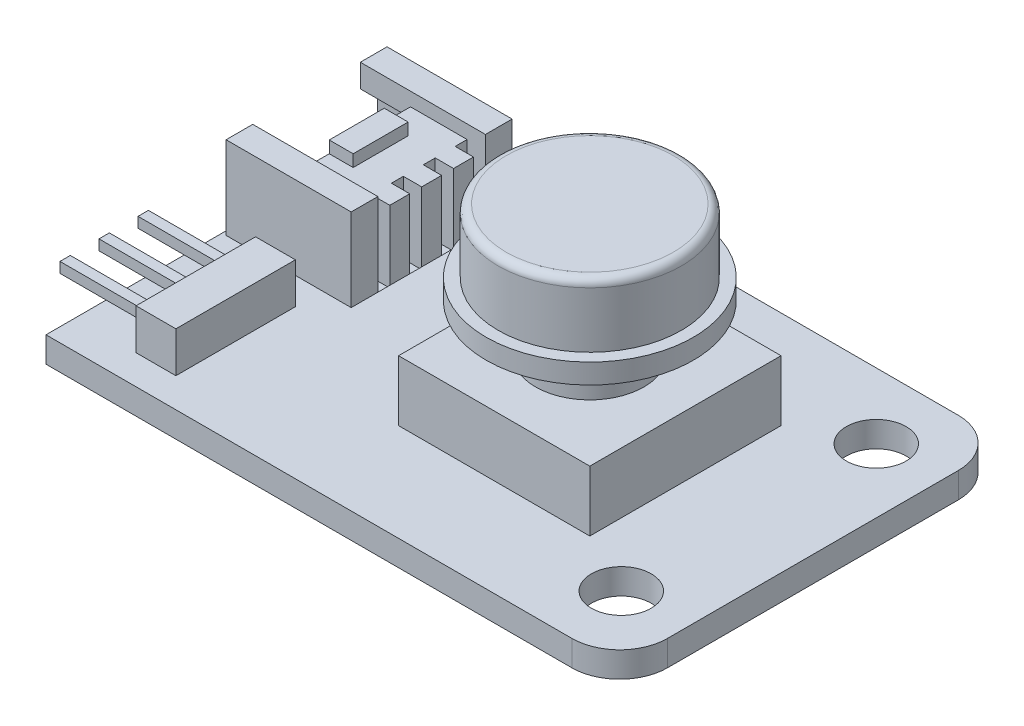
SolidWorks part; units mm, degrees
ref_plane "Front Plane" through (0, 0, 0) normal (0, 0, 1) x (1, 0, 0)
ref_plane "Top Plane" through (0, 0, 0) normal (0, 1, 0) x (1, 0, 0)
ref_plane "Right Plane" through (0, 0, 0) normal (1, 0, 0) x (0, 0, -1)
sketch "Sketch1" plane through (0, 0, 0) normal (0, 1, 0) x (1, 0, 0)
  line L0 (0, 0) -> (36, 0) construction
  line L1 (0, 12.125) -> (0, -12.125)
  line L2 (0, -12.125) -> (36, -12.125)
  line L3 (36, -12.125) -> (36, 12.125)
  line L4 (36, 12.125) -> (0, 12.125)
  dimension "D1" = 24.25
  dimension "D2" = 36
extrude "Boss-Extrude1" add sketch "Sketch1" along normal blind 1.6
sketch "Sketch2" plane through (0, 1.6, 0) normal (0, 1, 0) x (1, 0, 0)
  line L0 (0, 0) -> (36, 0) construction
  line L1 (36, -12.125) -> (36, 12.125) construction
  line L2 (31.975, -8) -> (31.975, 8) construction
  circle A0 centre (31.975, 8) radius 1.875
  circle A1 centre (31.975, -8) radius 1.875
  dimension "D1" = 12.25
  dimension "D2" = 3.75
  dimension "D3" = 2.15
extrude "Cut-Extrude1" cut sketch "Sketch2" against normal through all
fillet "Fillet1" radius 3 2 edges at (36, 0.8, -12.125) (36, 0.8, 12.125)
sketch "Sketch3" plane through (0, 1.6, 0) normal (0, 1, 0) x (1, 0, 0)
  line L0 (0, 0) -> (36, 0) construction
  line L1 (16, 6) -> (28, 6)
  line L2 (16, 6) -> (16, -6)
  line L3 (16, -6) -> (28, -6)
  line L4 (28, 6) -> (28, -6)
  line L5 (16, 6) -> (28, -6) construction
  line L6 (16, -6) -> (28, 6) construction
  line L7 (36, -9.125) -> (36, 9.125) construction
  point P0 (22, 0)
  dimension "D1" = 12
  dimension "D2" = 8
extrude "Boss-Extrude2" add sketch "Sketch3" along normal blind 3.8
sketch "Sketch4" plane through (0, 5.4, 0) normal (0, 1, 0) x (1, 0, 0)
  line L0 (16, 0) -> (28, 0) construction
  line L1 (16, 6) -> (16, -6) construction
  line L2 (28, -6) -> (28, 6) construction
  line L3 (22, 6) -> (22, -6) construction
  line L4 (28, 6) -> (16, 6) construction
  line L5 (16, -6) -> (28, -6) construction
  circle A0 centre (22, 0) radius 3.4
  dimension "D1" = 6.8
extrude "Boss-Extrude3" add sketch "Sketch4" along normal blind 3
sketch "Sketch5" plane through (0, 8.4, 0) normal (0, 1, 0) x (1, 0, 0)
  circle A0 centre (22, 0) radius 6.5
  dimension "D1" = 13
extrude "Boss-Extrude4" add sketch "Sketch5" along normal blind 1.25
sketch "Sketch6" plane through (0, 9.65, 0) normal (0, 1, 0) x (1, 0, 0)
  circle A0 centre (22, 0) radius 5.75
  dimension "D1" = 11.5
extrude "Boss-Extrude5" add sketch "Sketch6" along normal blind 4
fillet "Fillet2" radius 0.5 1 edges at (22, 13.65, 5.75)
sketch "Sketch7" plane through (0, 1.6, 0) normal (0, 1, 0) x (1, 0, 0)
  line L0 (0, 12.125) -> (0, -12.125) construction
  line L1 (3.8, -2.775) -> (6.3, -2.775)
  line L2 (3.8, -2.775) -> (3.8, -10.275)
  line L3 (3.8, -10.275) -> (6.3, -10.275)
  line L4 (6.3, -2.775) -> (6.3, -10.275)
  line L5 (0, -12.125) -> (33, -12.125) construction
  dimension "D1" = 2.5
  dimension "D2" = 7.5
  dimension "D3" = 3.8
  dimension "D4" = 1.85
extrude "Boss-Extrude6" add sketch "Sketch7" along normal blind 2.55
sketch "Sketch8" plane through (3.8, 0, 0) normal (-1, 0, 0) x (0, 0, 1)
  line L0 (2.775, 2.875) -> (10.275, 2.875) construction
  line L1 (2.775, 4.15) -> (2.775, 1.6) construction
  line L2 (10.275, 4.15) -> (10.275, 1.6) construction
  line L4 (3.75, 3.2) -> (4.4, 3.2)
  line L5 (3.75, 3.2) -> (3.75, 2.55)
  line L6 (3.75, 2.55) -> (4.4, 2.55)
  line L7 (4.4, 3.2) -> (4.4, 2.55)
  line L8 (3.75, 3.2) -> (4.4, 2.55) construction
  line L9 (3.75, 2.55) -> (4.4, 3.2) construction
  line L10 (6.2, 3.2) -> (6.85, 3.2)
  line L11 (6.2, 3.2) -> (6.2, 2.55)
  line L12 (6.2, 2.55) -> (6.85, 2.55)
  line L13 (6.85, 3.2) -> (6.85, 2.55)
  line L14 (6.2, 3.2) -> (6.85, 2.55) construction
  line L15 (6.2, 2.55) -> (6.85, 3.2) construction
  line L16 (8.65, 3.2) -> (9.3, 3.2)
  line L17 (8.65, 3.2) -> (8.65, 2.55)
  line L18 (8.65, 2.55) -> (9.3, 2.55)
  line L19 (9.3, 3.2) -> (9.3, 2.55)
  line L20 (8.65, 3.2) -> (9.3, 2.55) construction
  line L21 (8.65, 2.55) -> (9.3, 3.2) construction
  point P6 (4.075, 2.875)
  point P11 (6.525, 2.875)
  point P16 (8.975, 2.875)
  dimension "D1" = 0.65
  dimension "D2" = 1.8
  dimension "D3" = 1.8
extrude "Boss-Extrude7" add sketch "Sketch8" along normal blind 5.75
ref_plane "Plane1" through (0.25, 0, 0) normal (-1, 0, 0) x (0, 0, 1)
sketch "Sketch9" plane through (0.25, 0, 0) normal (-1, 0, 0) x (0, 0, 1)
  line L0 (-12.125, 1.6) -> (12.125, 1.6) construction
  line L1 (-9.025, 1.6) -> (1.075, 1.6)
  line L2 (-9.025, 1.6) -> (-9.025, 6.8)
  line L3 (-9.025, 6.8) -> (-7.35, 6.8)
  line L4 (1.075, 1.6) -> (1.075, 6.8)
  line L5 (-3.975, 1.6) -> (-3.975, 5.95) construction
  line L6 (-12.125, 1.6) -> (-12.125, 0) construction
  line L7 (-7.35, 6.8) -> (-7.35, 5.95)
  line L8 (-7.35, 5.95) -> (-0.6, 5.95)
  line L9 (-0.6, 6.8) -> (-0.6, 5.95)
  line L10 (-0.6, 6.8) -> (1.075, 6.8)
  point P13 (-8.1875, 6.8)
  dimension "D1" = 10.1
  dimension "D2" = 6.75
  dimension "D3" = 0.85
  dimension "D4" = 5.2
  dimension "D5" = 3.1
extrude "Boss-Extrude8" add sketch "Sketch9" against normal blind 7.85
sketch "Sketch10" plane through (0.25, 0, 0) normal (-1, 0, 0) x (0, 0, 1)
  line L24 (-8.425, 6.2) -> (-8.425, 2.2)
  line L25 (-8.425, 2.2) -> (0.475, 2.2)
  line L26 (0.475, 2.2) -> (0.475, 6.2)
  line L27 (0.475, 6.2) -> (0, 6.2)
  line L28 (0, 6.2) -> (0, 5.35)
  line L29 (0, 5.35) -> (-7.95, 5.35)
  line L30 (-7.95, 5.35) -> (-7.95, 6.2)
  line L31 (-7.95, 6.2) -> (-8.425, 6.2)
  line L32 (-8.425, 6.2) -> (-8.425, 2.2)
  line L33 (-8.425, 2.2) -> (0.475, 2.2)
  line L34 (0.475, 2.2) -> (0.475, 6.2)
  line L35 (0.475, 6.2) -> (0, 6.2)
  line L36 (0, 6.2) -> (0, 5.35)
  line L37 (0, 5.35) -> (-7.95, 5.35)
  line L38 (-7.95, 5.35) -> (-7.95, 6.2)
  line L39 (-7.95, 6.2) -> (-8.425, 6.2)
  dimension "D1" = 0.6
extrude "Cut-Extrude2" cut sketch "Sketch10" against normal blind 6.2
sketch "Sketch11" plane through (0, 5.95, 0) normal (0, 1, 0) x (1, 0, 0)
  line L0 (8.1, 0.6) -> (0.25, 0.6) construction
  line L1 (0.25, 7.35) -> (3.4, 7.35)
  line L2 (0.25, 7.35) -> (0.25, 0.6)
  line L3 (0.25, 0.6) -> (3.4, 0.6)
  line L4 (3.4, 7.35) -> (3.4, 0.6)
  dimension "D1" = 3.15
extrude "Cut-Extrude3" cut sketch "Sketch11" against normal blind 1
sketch "Sketch12" plane through (0, 2.2, 0) normal (0, 1, 0) x (1, 0, 0)
  line L0 (8.1, 7.35) -> (0.25, 7.35) construction
  line L1 (0.25, 0.6) -> (1.5, 0.6)
  line L2 (0.25, 0.6) -> (0.25, 7.35)
  line L3 (0.25, 7.35) -> (1.5, 7.35)
  line L4 (1.5, 0.6) -> (1.5, 7.35)
  dimension "D1" = 1.25
extrude "Cut-Extrude4" cut sketch "Sketch12" against normal blind 0.6
sketch "Sketch13" plane through (0, 5.95, 0) normal (0, 1, 0) x (1, 0, 0)
  line L0 (8.1, 3.975) -> (3.4, 3.975) construction
  line L1 (8.1, 0.6) -> (8.1, 7.35) construction
  line L2 (3.4, 0.6) -> (3.4, 7.35) construction
  line L4 (3.4, 5.7) -> (4.9, 5.7)
  line L5 (3.4, 5.7) -> (3.4, 2.25)
  line L6 (3.4, 2.25) -> (4.9, 2.25)
  line L7 (4.9, 5.7) -> (4.9, 2.25)
  dimension "D1" = 3.45
  dimension "D2" = 1.5
extrude "Boss-Extrude9" add sketch "Sketch13" along normal blind 0.75
sketch "Sketch14" plane through (0, 5.95, 0) normal (0, 1, 0) x (1, 0, 0)
  line L0 (8.1, 9.025) -> (8.1, -1.075) construction
  line L1 (8.1, 7.35) -> (6.95, 7.35)
  line L2 (8.1, 7.35) -> (8.1, 6.6)
  line L3 (8.1, 6.6) -> (6.95, 6.6)
  line L4 (6.95, 7.35) -> (6.95, 6.6)
  line L5 (8.1, 5.35) -> (6.95, 5.35)
  line L6 (8.1, 5.35) -> (8.1, 4.6)
  line L7 (8.1, 4.6) -> (6.95, 4.6)
  line L8 (6.95, 5.35) -> (6.95, 4.6)
  line L9 (3.4, 3.975) -> (8.1, 3.975) construction
  line L10 (3.4, 5.7) -> (3.4, 2.25) construction
  line L11 (6.95, 2.6) -> (6.95, 3.35)
  line L12 (8.1, 3.35) -> (6.95, 3.35)
  line L13 (8.1, 2.6) -> (8.1, 3.35)
  line L14 (8.1, 2.6) -> (6.95, 2.6)
  line L15 (6.95, 0.6) -> (6.95, 1.35)
  line L16 (8.1, 1.35) -> (6.95, 1.35)
  line L17 (8.1, 0.6) -> (8.1, 1.35)
  line L18 (8.1, 0.6) -> (6.95, 0.6)
  dimension "D1" = 1.15
  dimension "D2" = 0.75
  dimension "D3" = 1.25
  dimension "D4" = 1.25
extrude "Cut-Extrude5" cut sketch "Sketch14" against normal blind 4.5
sketch "Sketch15" plane through (0, 0, 0) normal (0, -1, 0) x (1, 0, 0)
  line L0 (0, 0) -> (36, 0) construction
  line L1 (36, 9.125) -> (36, -9.125) construction
  line L2 (25, -6.6) -> (25, -5.6)
  line L3 (19, 6.6) -> (20, 6.6)
  line L4 (19, 6.6) -> (19, 5.6)
  line L5 (19, 5.6) -> (20, 5.6)
  line L6 (20, 6.6) -> (20, 5.6)
  line L7 (24, 6.6) -> (25, 6.6)
  line L8 (24, 6.6) -> (24, 5.6)
  line L9 (24, 5.6) -> (25, 5.6)
  line L10 (25, 6.6) -> (25, 5.6)
  line L11 (24, -5.6) -> (25, -5.6)
  line L12 (24, -6.6) -> (24, -5.6)
  line L13 (24, -6.6) -> (25, -6.6)
  line L14 (20, -6.6) -> (20, -5.6)
  line L15 (19, -5.6) -> (20, -5.6)
  line L16 (19, -6.6) -> (19, -5.6)
  line L17 (19, -6.6) -> (20, -6.6)
  dimension "D1" = 1
  dimension "D2" = 4
  dimension "D3" = 11.2
  dimension "D4" = 11
extrude "Boss-Extrude10" add sketch "Sketch15" along normal blind 1.6
sketch "Sketch16" plane through (0, 0, 0) normal (0, -1, 0) x (1, 0, 0)
  line L0 (7.25, 12.125) -> (7.25, -12.125) construction
  line L1 (33, -12.125) -> (0, -12.125) construction
  line L2 (0, 12.125) -> (33, 12.125) construction
  line L3 (0, -12.125) -> (0, 12.125) construction
  line L4 (7.25, 9.325) -> (8, 9.325)
  line L5 (7.25, 9.325) -> (7.25, 8.575)
  line L6 (7.25, 8.575) -> (8, 8.575)
  line L7 (8, 9.325) -> (8, 8.575)
  line L8 (7.25, 6.825) -> (8, 6.825)
  line L9 (7.25, 6.825) -> (7.25, 6.075)
  line L10 (7.25, 6.075) -> (8, 6.075)
  line L11 (8, 6.825) -> (8, 6.075)
  line L12 (7.25, 4.325) -> (8, 4.325)
  line L13 (7.25, 4.325) -> (7.25, 3.575)
  line L14 (7.25, 3.575) -> (8, 3.575)
  line L15 (8, 4.325) -> (8, 3.575)
  line L16 (7.25, -0.275) -> (8, -0.275)
  line L17 (7.25, -0.275) -> (7.25, -1.025)
  line L18 (7.25, -1.025) -> (8, -1.025)
  line L19 (8, -0.275) -> (8, -1.025)
  line L20 (7.25, -2.425) -> (8, -2.425)
  line L21 (7.25, -2.425) -> (7.25, -3.175)
  line L22 (7.25, -3.175) -> (8, -3.175)
  line L23 (8, -2.425) -> (8, -3.175)
  line L24 (7.25, -4.575) -> (8, -4.575)
  line L25 (7.25, -4.575) -> (7.25, -5.325)
  line L26 (7.25, -5.325) -> (8, -5.325)
  line L27 (8, -4.575) -> (8, -5.325)
  line L28 (7.25, -6.725) -> (8, -6.725)
  line L29 (7.25, -6.725) -> (7.25, -7.475)
  line L30 (7.25, -7.475) -> (8, -7.475)
  line L31 (8, -6.725) -> (8, -7.475)
  dimension "D1" = 0.75
  dimension "D2" = 7.25
  dimension "D3" = 1.75
  dimension "D4" = 1.75
  dimension "D5" = 4.65
  dimension "D6" = 2.8
  dimension "D7" = 1.4
  dimension "D8" = 1.4
  dimension "D9" = 1.4
extrude "Boss-Extrude11" add sketch "Sketch16" along normal blind 2
